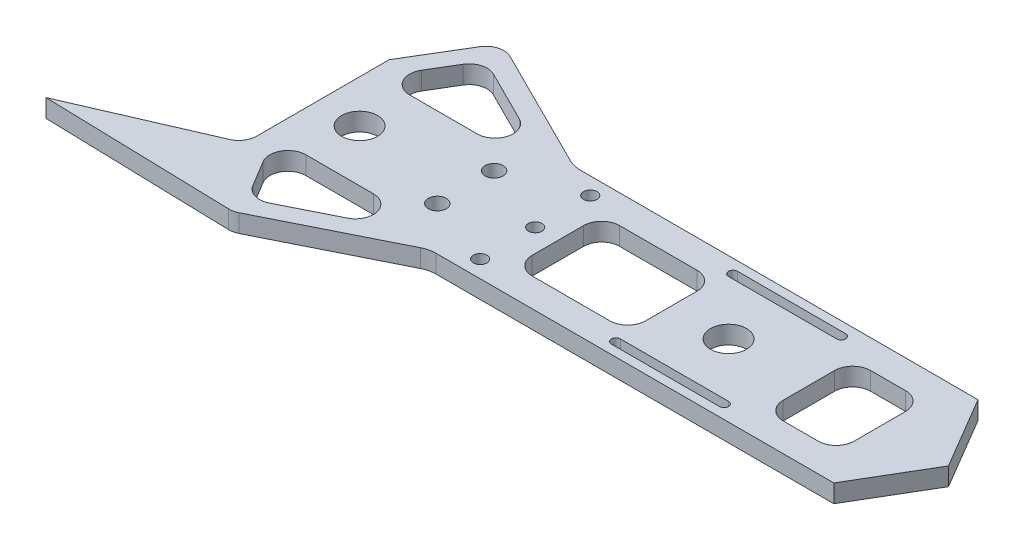
SolidWorks part; units mm, degrees
material "AISI 1020"
ref_plane "Alzado" through (0, 0, 0) normal (0, 0, 1) x (1, 0, 0)
ref_plane "Planta" through (0, 0, 0) normal (0, 1, 0) x (1, 0, 0)
ref_plane "Vista lateral" through (0, 0, 0) normal (1, 0, 0) x (0, 0, -1)
sketch "Croquis1" plane through (0, 0, 0) normal (0, 1, 0) x (1, 0, 0)
  line L0 (37.5, -25.4) -> (52.5, 0)
  line L3 (-45.9466, -25.4) -> (37.5, -25.4) construction
  line L4 (37.5, 25.4) -> (37.5, -25.4) construction
  line L5 (52.5, 0) -> (37.5, 25.4)
  line L6 (0, 0) -> (37.5, 0) construction
  line L11 (0, 0) -> (0, -19.05) construction
  line L12 (-19.05, 19.05) -> (19.05, 19.05) construction
  line L13 (-19.05, 19.05) -> (-19.05, -19.05) construction
  line L14 (-19.05, -19.05) -> (19.05, -19.05) construction
  line L15 (19.05, 19.05) -> (19.05, -19.05) construction
  line L16 (37.5, 25.4) -> (-105, 25.4)
  line L20 (-105, -25.4) -> (37.5, -25.4)
  line L21 (0, 0) -> (-170, 0) construction
  line L38 (-105, -25.4) -> (-105, 25.4) construction
  line L41 (-105, -25.4) -> (-149.7468, -47.7317)
  line L42 (-158.0248, -45.3215) -> (-170, -25.4) construction
  line L43 (-170, -25.4) -> (-170, 25.4)
  line L44 (-170, 25.4) -> (-158.0248, 45.3215)
  line L45 (-149.7468, 47.7317) -> (-105, 25.4)
  line L46 (-155, -50.3534) -> (-155, 50.3534) construction
  line L47 (-170, 25.4) -> (-105, 25.4) construction
  line L48 (-105, -25.4) -> (-170, -25.4) construction
  line L49 (-170, -25.4) -> (-218.8932, -46.6132)
  line L50 (-218.8932, -46.6132) -> (-152.7537, -48.3977)
  line L51 (-173.3511, 48.4) -> (-113.9016, 48.4) construction
  line L52 (-129.0451, 30.3033) -> (-147.3292, 39.4283)
  line L53 (-155.6072, 37.0181) -> (-161.0924, 27.8931)
  line L54 (-155.65, 18.2716) -> (-131.8807, 18.2716)
  line L55 (-182.7394, 6.35) -> (-126.5741, 6.35) construction
  line L56 (-162, 48.4) -> (-162, -3.791) construction
  line L57 (-129.0451, -30.3033) -> (-147.3292, -39.4283)
  line L58 (-155.6072, -37.0181) -> (-161.0924, -27.8931)
  line L59 (-155.65, -18.2716) -> (-131.8807, -18.2716)
  line L60 (-135, 6.35) -> (-115, 6.35) construction
  line L61 (-115, -6.35) -> (-135, -6.35) construction
  line L68 (-43.5252, -9.4) -> (-51.6516, -9.4) construction
  circle A0 centre (0, 0) radius 6.35 construction
  circle A1 centre (0, 0) radius 52.5 construction
  circle A11 centre (-155, 0) radius 6.35
  circle A12 centre (-155, 0) radius 44.45 construction
  arc A13 (-149.7468, -47.7317) -> (-158.0248, -45.3215) centre (-152.5824, -42.05) cw construction
  arc A14 (-158.0248, 45.3215) -> (-149.7468, 47.7317) centre (-152.5824, 42.05) cw
  arc A15 (-152.7537, -48.3977) -> (-149.7468, -47.7317) centre (-152.5824, -42.05) ccw
  arc A16 (-129.0451, 30.3033) -> (-131.8807, 18.2716) centre (-131.8807, 24.6216) cw
  arc A17 (-161.0924, 27.8931) -> (-155.65, 18.2716) centre (-155.65, 24.6216) ccw
  arc A18 (-147.3292, 39.4283) -> (-155.6072, 37.0181) centre (-150.1648, 33.7466) ccw
  arc A19 (-129.0451, -30.3033) -> (-131.8807, -18.2716) centre (-131.8807, -24.6216) ccw
  arc A20 (-147.3292, -39.4283) -> (-155.6072, -37.0181) centre (-150.1648, -33.7466) cw
  arc A21 (-161.0924, -27.8931) -> (-155.65, -18.2716) centre (-155.65, -24.6216) cw
  arc A22 (-135, 6.35) -> (-135, -6.35) centre (-135, 0) ccw construction
  arc A23 (-115, -6.35) -> (-115, 6.35) centre (-115, 0) ccw construction
  circle A32 centre (-25, 0) radius 50.8 construction
  circle A33 centre (-25, 0) radius 6.35
  point P19 (19.05, 0)
  point P20 (-170, 0)
  dimension "D1" = 12.7
  dimension "D2" = 105
  dimension "D7" = 6.35
  dimension "D10" = 23
  dimension "D11" = 25
  dimension "D9" = 15
  dimension "D15" = 20
  dimension "D3" = 50
  dimension "D4" = 88.9
  dimension "D12" = 12.7
  dimension "D13" = 6.35
  dimension "D18" = 6.35
  dimension "D20" = 101.6
  dimension "D5" = 50.8
  dimension "D6" = 15
  dimension "D8" = 38.1
  dimension "D14" = 8
  dimension "D16" = 10
  dimension "D17" = 105
  dimension "D19" = 80
  dimension "D23" = 16
extrude "Saliente-Extruir1" add sketch "Croquis1" along normal blind 6.35
sketch "Croquis4" plane through (0, 6.35, 0) normal (0, 1, 0) x (1, 0, 0)
  line L0 (-105, -25.4) -> (37.5, -25.4) construction
  line L1 (-101.825, -25.4) -> (-105, -25.4) construction
  line L2 (-101.825, -25.4) -> (-101.825, 25.4) construction
  line L3 (-101.825, 25.4) -> (-105, 25.4) construction
  line L4 (-105, -25.4) -> (-105, 25.4) construction
  line L5 (37.5, 25.4) -> (-105, 25.4) construction
  line L6 (37.5, -25.4) -> (34.325, -25.4)
  line L7 (37.5, -25.4) -> (37.5, 25.4)
  line L8 (37.5, 25.4) -> (34.325, 25.4)
  line L9 (34.325, -25.4) -> (34.325, 25.4)
  dimension "D1" = 3.175
extrude "Cortar-Extruir1" [suppressed] cut sketch "Croquis4" against normal blind 3.175
sketch "Croquis5" plane through (0, 6.35, 0) normal (0, 1, 0) x (1, 0, 0)
  line L0 (-44.05, 22.225) -> (-5.95, 22.225)
  line L1 (-5.95, 19.05) -> (-44.05, 19.05)
  line L2 (-19.05, 19.05) -> (19.05, 19.05) construction
  line L3 (-25, 0) -> (-25, 19.05) construction
  line L4 (-19.05, 0) -> (37.5, 0) construction
  line L5 (-19.05, 19.05) -> (-19.05, -19.05) construction
  line L6 (-5.95, -19.05) -> (-44.05, -19.05)
  line L7 (-44.05, -22.225) -> (-5.95, -22.225)
  arc A0 (-5.95, 19.05) -> (-5.95, 22.225) centre (-5.95, 20.6375) ccw
  arc A1 (-44.05, 22.225) -> (-44.05, 19.05) centre (-44.05, 20.6375) ccw
  arc A2 (-44.05, -22.225) -> (-44.05, -19.05) centre (-44.05, -20.6375) cw
  arc A3 (-5.95, -19.05) -> (-5.95, -22.225) centre (-5.95, -20.6375) cw
  dimension "D1" = 1.5875
  dimension "D2" = 38.1
extrude "Cortar-Extruir2" cut sketch "Croquis5" against normal through all
sketch "Croquis7" plane through (0, 6.35, 0) normal (0, 1, 0) x (1, 0, 0)
  line L1 (-78.775, 15.4) -> (-51.475, 15.4)
  line L2 (-85.125, 9.05) -> (-85.125, -9.05)
  line L3 (-78.775, -15.4) -> (-51.475, -15.4)
  line L4 (-45.125, 9.05) -> (-45.125, -9.05)
  line L5 (-105, -25.4) -> (37.5, -25.4) construction
  line L6 (37.5, 25.4) -> (-105, 25.4) construction
  line L8 (9.675, 15.4) -> (21.975, 15.4)
  line L9 (3.325, 9.05) -> (3.325, -9.05)
  line L10 (9.675, -15.4) -> (21.975, -15.4)
  line L11 (28.325, 9.05) -> (28.325, -9.05)
  arc A0 (-51.475, -15.4) -> (-45.125, -9.05) centre (-51.475, -9.05) ccw
  arc A1 (-51.475, 15.4) -> (-45.125, 9.05) centre (-51.475, 9.05) cw
  arc A2 (-78.775, 15.4) -> (-85.125, 9.05) centre (-78.775, 9.05) ccw
  arc A3 (-85.125, -9.05) -> (-78.775, -15.4) centre (-78.775, -9.05) ccw
  arc A4 (21.975, -15.4) -> (28.325, -9.05) centre (21.975, -9.05) ccw
  arc A5 (21.975, 15.4) -> (28.325, 9.05) centre (21.975, 9.05) cw
  arc A6 (9.675, 15.4) -> (3.325, 9.05) centre (9.675, 9.05) ccw
  arc A7 (3.325, -9.05) -> (9.675, -15.4) centre (9.675, -9.05) ccw
  point P26 (28.325, -15.4)
  dimension "D1" = 6.35
  dimension "D6" = 6.35
  dimension "D2" = 122.625
  dimension "D3" = 10
  dimension "D4" = 10
  dimension "D5" = 40
  dimension "D7" = 25
  dimension "D8" = 9.175
extrude "Cortar-Extruir3" cut sketch "Croquis7" against normal through all
fillet "Redondeo1" radius 10 2 edges at (-105, 3.175, -25.4) (-105, 3.175, 25.4)
sketch "Croquis8" plane through (0, 6.35, 0) normal (0, 1, 0) x (1, 0, 0)
  line L0 (-93.125, -25.4) -> (-93.125, 25.4) construction
  line L1 (-102.6433, -25.4) -> (37.5, -25.4) construction
  line L2 (37.5, 25.4) -> (-102.6433, 25.4) construction
  line L3 (-85.125, 9.05) -> (-85.125, -9.05) construction
  line L4 (37.5, 25.4) -> (-102.6433, 25.4) construction
  line L5 (-102.6433, -25.4) -> (37.5, -25.4) construction
  circle A0 centre (-93.125, 0) radius 2.3813
  circle A1 centre (-93.125, 19.4) radius 2.3813
  circle A2 centre (-93.125, -19.4) radius 2.3813
  dimension "D1" = 4.7625
  dimension "D2" = 6
  dimension "D3" = 6
  dimension "D4" = 8
extrude "Cortar-Extruir4" cut sketch "Croquis8" against normal through all
fillet "Redondeo2" radius 6.35 1 edges at (-170, 3.175, 25.4)
sketch "Croquis9" plane through (0, 6.35, 0) normal (0, 1, 0) x (1, 0, 0)
  line L0 (-218.8932, -46.6132) -> (-152.7537, -48.3977) construction
  line L1 (-218.8932, -46.6132) -> (-173.8226, -27.0585) construction
  line L2 (-170, 25.4) -> (-170, -37.1496)
  line L3 (-170, 25.4) -> (-170, -21.2332) construction
  circle A0 centre (-170, -37.1496) radius 10.7788 construction
  circle A1 centre (-170, -37.1496) radius 4.7625
  dimension "D1" = 9.525
extrude "Cortar-Extruir5" [suppressed] cut sketch "Croquis9" against normal blind 10
sketch "Croquis10" plane through (0, 6.35, 0) normal (0, 1, 0) x (1, 0, 0)
  line L0 (0, 0) -> (-117.6117, 0) construction
  line L1 (-117.6117, 10) -> (-117.6117, -10)
  circle A0 centre (-117.6117, -10) radius 3.175
  circle A1 centre (-117.6117, 10) radius 3.175
  point P6 (0, 0)
  point P8 (0, 0)
  dimension "D2" = 6.35
  dimension "D1" = 20
  dimension "D3" = 117.6117
extrude "Cortar-Extruir6" cut sketch "Croquis10" against normal through all
